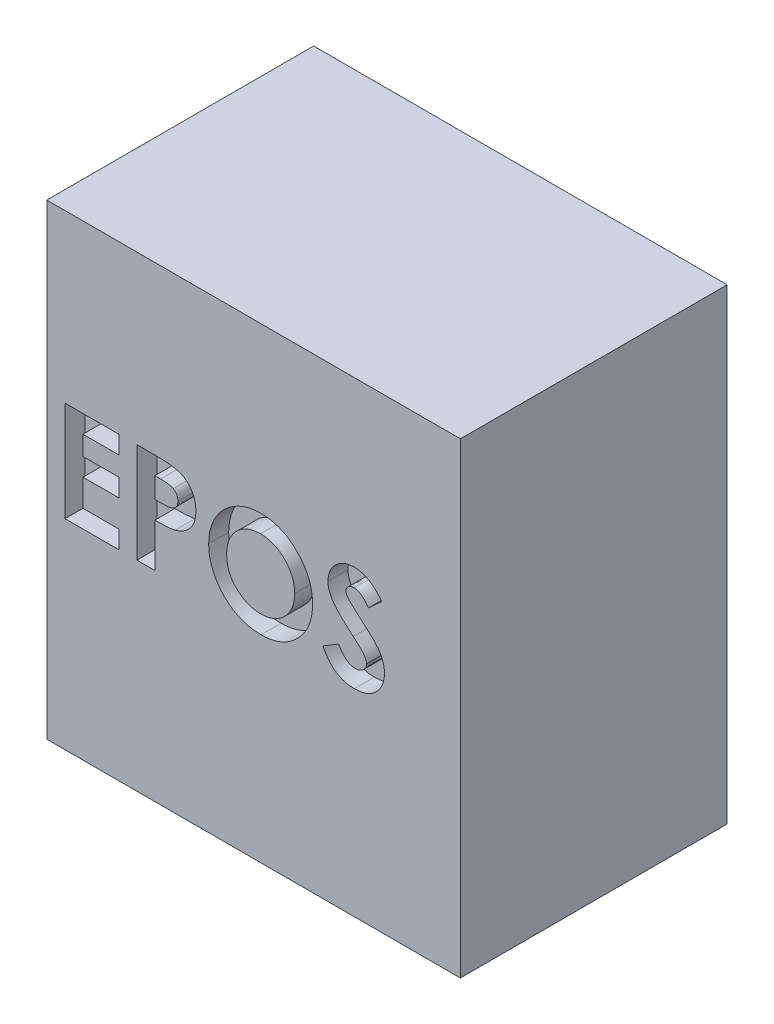
SolidWorks part; units mm, degrees
ref_plane "正面" through (0, 0, 0) normal (0, 0, 1) x (1, 0, 0)
ref_plane "平面" through (0, 0, 0) normal (0, 1, 0) x (1, 0, 0)
ref_plane "右側面" through (0, 0, 0) normal (1, 0, 0) x (0, 0, -1)
sketch "ｽｹｯﾁ1" plane through (0, 0, 0) normal (0, 0, 1) x (1, 0, 0)
  line L1 (0, 0) -> (62, 0)
  line L2 (0, 0) -> (0, 70)
  line L3 (0, 70) -> (62, 70)
  line L4 (62, 0) -> (62, 70)
  dimension "D1" = 62
  dimension "D2" = 70
extrude "ﾎﾞｽ - 押し出し1" add sketch "ｽｹｯﾁ1" along normal blind 40
sketch "ｽｹｯﾁ2" plane through (0, 0, 40) normal (0, 0, 1) x (1, 0, 0)
  line L1 (0, 70) -> (0, 0) construction
  line L2 (0, 0) -> (62, 0) construction
  text T0 "<b>EPOS</b>" font "Century Gothic" height 15
  dimension "D1" = 1
  dimension "D2" = 30
extrude "ｶｯﾄ - 押し出し1" cut sketch "ｽｹｯﾁ2" against normal blind 3
